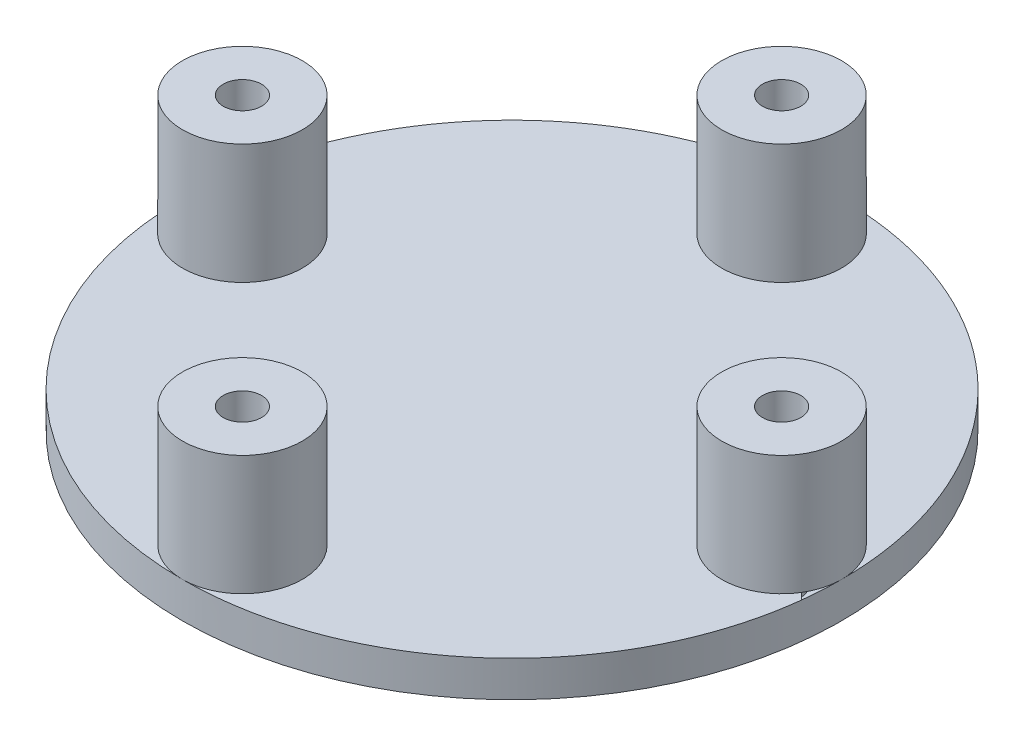
SolidWorks part; units mm, degrees
ref_plane "Front Plane" through (0, 0, 0) normal (0, 0, 1) x (1, 0, 0)
ref_plane "Top Plane" through (0, 0, 0) normal (0, 1, 0) x (1, 0, 0)
ref_plane "Right Plane" through (0, 0, 0) normal (1, 0, 0) x (0, 0, -1)
sketch "Sketch1" plane through (0, 0, 0) normal (0, 1, 0) x (1, 0, 0)
  circle A0 centre (0, 0) radius 27.5
  dimension "D1" = 55
extrude "Boss-Extrude1" add sketch "Sketch1" along normal blind 3
sketch "Sketch3" plane through (0, 3, 0) normal (0, 1, 0) x (1, 0, 0)
  circle A0 centre (0, 0) radius 22.5 construction
  circle A1 centre (0, 22.5) radius 5
  circle A2 centre (22.5, 0) radius 5
  circle A3 centre (0, -22.5) radius 5
  circle A4 centre (-22.5, 0) radius 5
  point P14 (0, 0)
  dimension "D1" = 45
  dimension "D2" = 4
  dimension "D3" = 10
extrude "Boss-Extrude2" add sketch "Sketch3" along normal blind 10
sketch "Sketch4" plane through (0, 13, 0) normal (0, 1, 0) x (1, 0, 0)
  circle A0 centre (0, 22.5) radius 1.6
  circle A1 centre (22.5, 0) radius 1.6
  circle A2 centre (0, -22.5) radius 1.6
  circle A3 centre (-22.5, 0) radius 1.6
  point P12 (0, 0)
  dimension "D1" = 3.2
  dimension "D2" = 4
extrude "Cut-Extrude1" cut sketch "Sketch4" against normal through all
